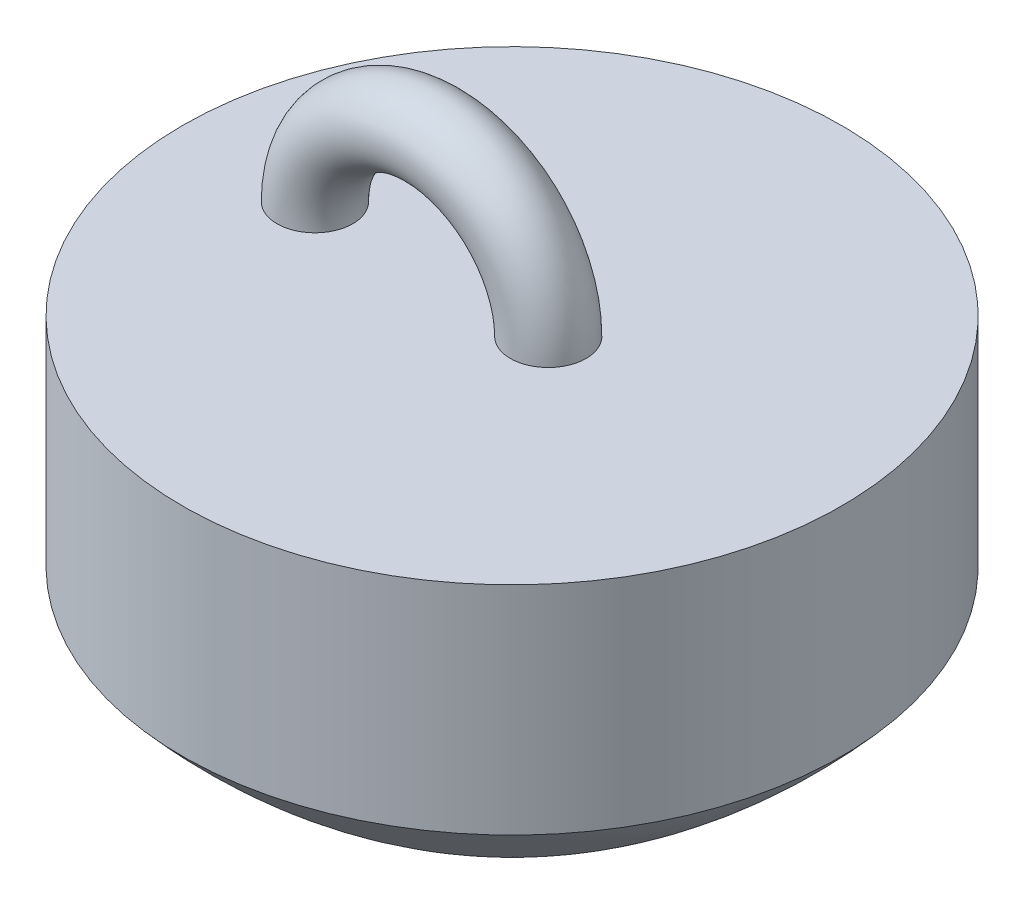
SolidWorks part; units mm, degrees
material "PLA (100% Honeyvone infill)"
ref_plane "Front Plane" through (0, 0, 0) normal (0, 0, 1) x (1, 0, 0)
ref_plane "Top Plane" through (0, 0, 0) normal (0, 1, 0) x (1, 0, 0)
ref_plane "Right Plane" through (0, 0, 0) normal (1, 0, 0) x (0, 0, -1)
sketch "Sketch1" plane through (0, 0, 0) normal (0, 0, 1) x (1, 0, 0)
  line L17 (14.605, -9.0862) -> (14.605, -26.6048)
  line L21 (0.254, -9.0862) -> (14.605, -9.0862)
  line L22 (0.254, -9.0862) -> (0.254, -18.5248)
  arc A3 (0.254, -18.5248) -> (14.605, -26.6048) centre (18.9031, -2.1866) ccw
  point P1 (0, -9.0862)
  point P2 (0.254, -9.0862)
  point P3 (-0.254, 0.0791)
  point P5 (-7.6214, 27.9923)
  point P7 (1.926, 0.0791)
  dimension "D1" = 0.254
  dimension "D2" = 9.4386
revolve "Revolve1" add sketch "Sketch1" angle 360 about L17
sketch "Sketch2" plane through (0, -9.0862, 0) normal (0, 1, 0) x (1, 0, 0)
  line L0 (-13.2674, 0) -> (13.2674, 0) construction
  circle A0 centre (6.0196, 0) radius 1.651
  circle A1 centre (16.1796, 0) radius 1.651
  dimension "D1" = 3.302
  dimension "D2" = 2
sketch "Sketch3" plane through (0, 0, 0) normal (0, 0, 1) x (1, 0, 0)
  line L0 (7.6706, -9.0862) -> (4.3686, -9.0862) construction
  line L1 (17.8306, -9.0862) -> (14.5286, -9.0862) construction
  arc A0 (6.0196, -9.0862) -> (16.1796, -9.0862) centre (11.0996, -9.0862) cw
sweep "Sweep1" add profiles "Sketch2" path "Sketch3"
